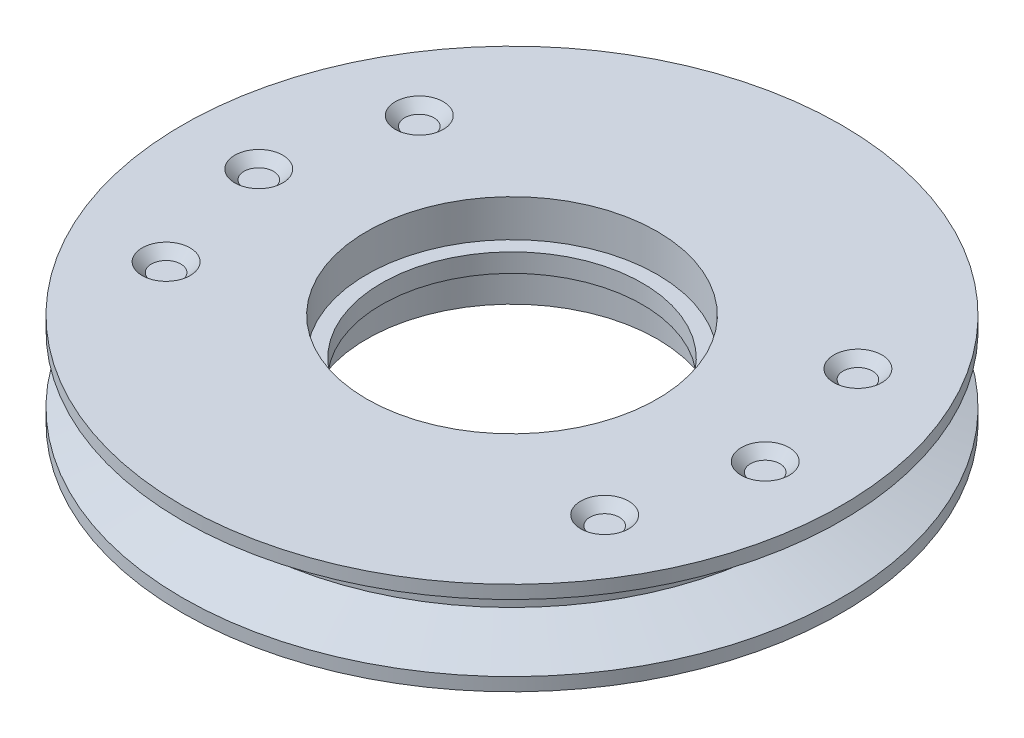
SolidWorks part; units mm, degrees
other "Marca1"
sketch "Croquis6" plane through (80, 12.5, 80) normal (0.541, 0.1937, 0.8184) x (0.8378, -0.0386, -0.5446)
material "Aleación 1060"
ref_plane "Alzado" through (0, 0, 0) normal (0, 0, 1) x (1, 0, 0)
ref_plane "Planta" through (0, 0, 0) normal (0, 1, 0) x (1, 0, 0)
ref_plane "Vista lateral" through (0, 0, 0) normal (1, 0, 0) x (0, 0, -1)
sketch "Croquis5" plane through (0, 0, 0) normal (1, 0, 0) x (0, 0, -1)
  line L0 (0, 0) -> (39, 0) construction
  line L1 (0, 0) -> (0, 20.4077) construction
  line L2 (39, 12.5) -> (39, -12.5)
  line L3 (39, -12.5) -> (88.5, -12.5)
  line L4 (88.5, -12.5) -> (88.5, -8.9596)
  line L5 (88.5, -8.9596) -> (73.5, -3.5)
  line L6 (73.5, -3.5) -> (73.5, 3.5)
  line L7 (73.5, 3.5) -> (88.5, 8.9596)
  line L13 (39, 12.5) -> (88.5, 12.5)
  line L14 (88.5, 12.5) -> (88.5, 8.9596)
  point P7 (39, 0)
  dimension "D1" = 39
  dimension "D2" = 25
  dimension "D3" = 88.5
  dimension "D4" = 15
  dimension "D5" = 7
  dimension "D6" = 9
  dimension "D7" = 40
  dimension "D8" = 20
revolve "Revolución2" add sketch "Croquis5" angle 360 about L1
sketch "Croquis9" plane through (0, 12.5, 0) normal (0, 1, 0) x (1, 0, 0)
  line L0 (0, 0) -> (68, 0) construction
  line L1 (0, 0) -> (58.8897, 34) construction
  line L2 (0, 0) -> (0, 30.1625) construction
  circle A0 centre (0, 0) radius 68 construction
  circle A1 centre (58.8897, 34) radius 6.45
  circle A5 centre (68, 0) radius 6.45
  circle A6 centre (58.8897, -34) radius 6.45
  circle A7 centre (-58.8897, -34) radius 6.45
  circle A8 centre (-68, 0) radius 6.45
  circle A9 centre (-58.8897, 34) radius 6.45
  dimension "D1" = 136
  dimension "D3" = 12.9
  dimension "D4" = 12.9
  dimension "D2" = 30
extrude "Cortar-Extruir1" cut sketch "Croquis9" against normal blind 2.5 draft 45
sketch "Croquis10" plane through (0, 0, 0) normal (0, 1, 0) x (1, 0, 0)
  circle A0 centre (0, 0) radius 39
  circle A1 centre (0, 0) radius 35
  dimension "D1" = 70
extrude "Saliente-Extruir1" add sketch "Croquis10" along normal mid plane 5
